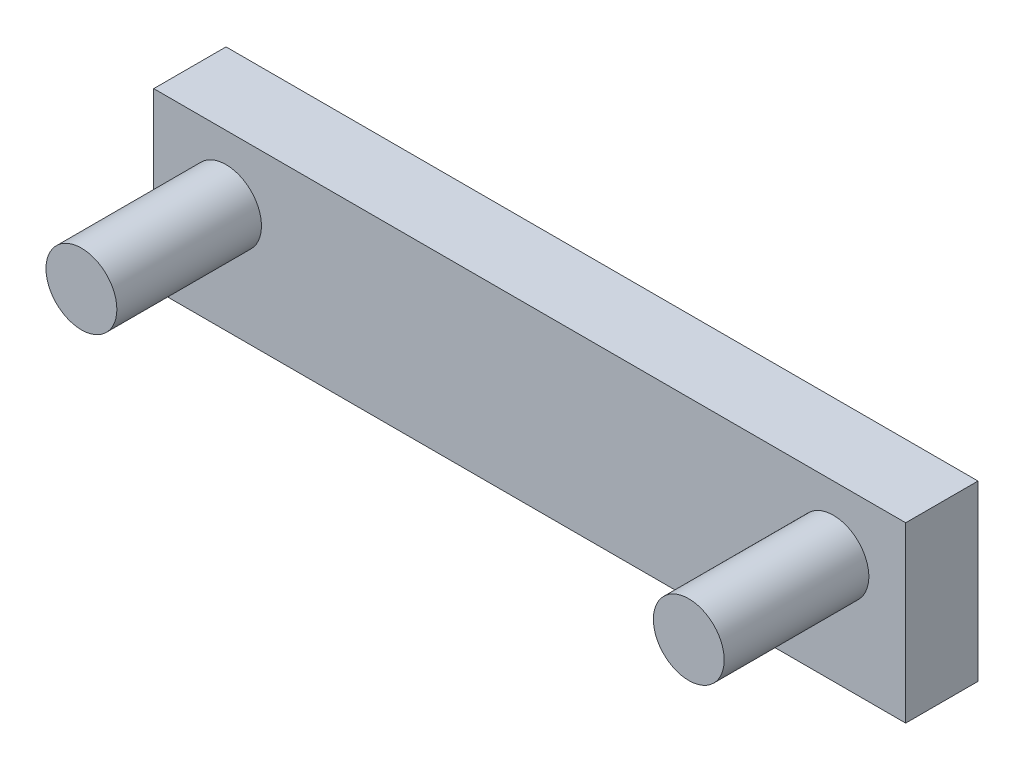
SolidWorks part; units mm, degrees
ref_plane "정면" through (0, 0, 0) normal (0, 0, 1) x (1, 0, 0)
ref_plane "윗면" through (0, 0, 0) normal (0, 1, 0) x (1, 0, 0)
ref_plane "우측면" through (0, 0, 0) normal (1, 0, 0) x (0, 0, -1)
sketch "스케치3" plane through (0, 0, 0) normal (0, 0, 1) x (1, 0, 0)
  line L0 (0, 7.5) -> (0, -7.5) construction
  line L1 (-26, 7.5) -> (26, 7.5)
  line L2 (-26, 7.5) -> (-26, -7.5)
  line L3 (-26, -7.5) -> (26, -7.5)
  line L4 (26, 7.5) -> (26, -7.5)
  circle A0 centre (-21, 0) radius 2.45
  circle A1 centre (21, 0) radius 2.45
  point P12 (-26, 0)
  point P15 (26, 0)
  point P18 (0, -7.5)
  dimension "D1" = 4.9
  dimension "D2" = 52
  dimension "D3" = 15
  dimension "D4" = 5
extrude "보스-돌출2" add sketch "스케치3" along normal blind 10 contours A1 | A0
sketch "스케치4" plane through (0, 0, 0) normal (0, 0, 1) x (1, 0, 0)
  line L1 (-26, -7.5) -> (26, -7.5)
  line L2 (-26, -7.5) -> (-26, 7.5)
  line L3 (-26, 7.5) -> (26, 7.5)
  line L4 (26, -7.5) -> (26, 7.5)
  line L5 (-26, -7.5) -> (26, 7.5) construction
  line L6 (-26, 7.5) -> (26, -7.5) construction
  point P0 (0, 0)
  dimension "D1" = 52
  dimension "D2" = 15
extrude "보스-돌출3" add sketch "스케치4" against normal blind 5
sketch "스케치5" plane through (0, 0, -5) normal (0, 0, -1) x (-1, 0, 0)
  line L0 (26, 7.5) -> (26, -7.5) construction
  line L1 (-26, 7.5) -> (26, 7.5)
  line L2 (-26, 7.5) -> (-26, 4.5)
  line L3 (-26, 4.5) -> (26, 4.5)
  line L4 (26, 7.5) -> (26, 4.5)
  dimension "D1" = 3
extrude "컷-돌출1" cut sketch "스케치5" against normal through all
